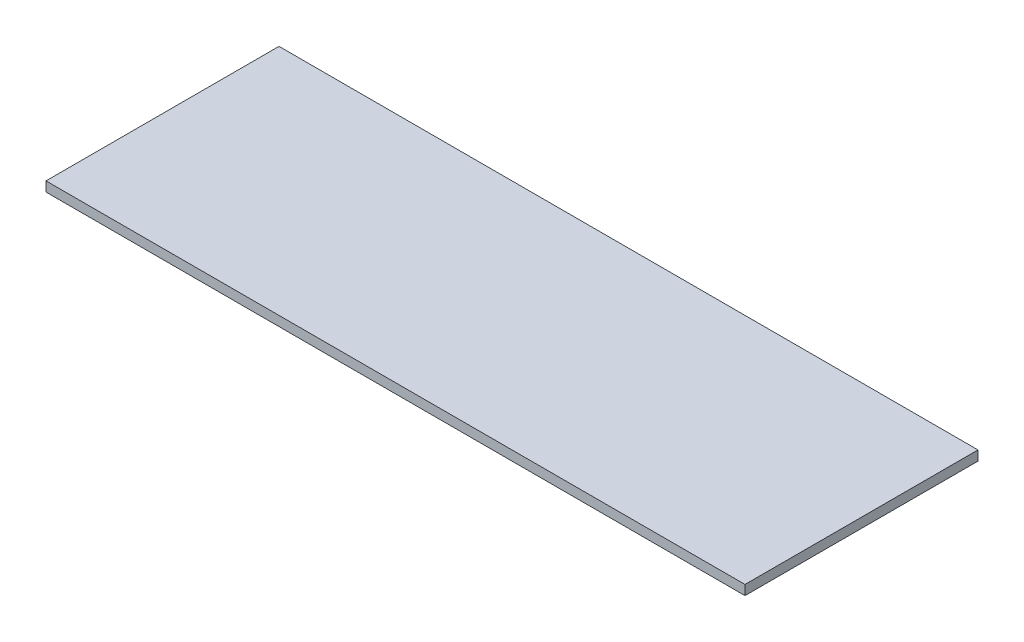
SolidWorks part; units mm, degrees
material "ASTM A36 Steel"
ref_plane "Front Plane" through (0, 0, 0) normal (0, 0, 1) x (1, 0, 0)
ref_plane "Top Plane" through (0, 0, 0) normal (0, 1, 0) x (1, 0, 0)
ref_plane "Right Plane" through (0, 0, 0) normal (1, 0, 0) x (0, 0, -1)
sketch "Sketch1" plane through (0, 0, 0) normal (0, 1, 0) x (1, 0, 0)
  line L1 (-114.3, -38.1) -> (114.3, -38.1)
  line L2 (-114.3, -38.1) -> (-114.3, 38.1)
  line L3 (-114.3, 38.1) -> (114.3, 38.1)
  line L4 (114.3, -38.1) -> (114.3, 38.1)
  line L5 (-114.3, -38.1) -> (114.3, 38.1) construction
  line L6 (-114.3, 38.1) -> (114.3, -38.1) construction
  line L7 (-114.3, 0) -> (114.3, 0) construction
  point P0 (0, 0)
  dimension "D1" = 228.6
  dimension "D2" = 76.2
extrude "Boss-Extrude1" add sketch "Sketch1" along normal blind 3.175
